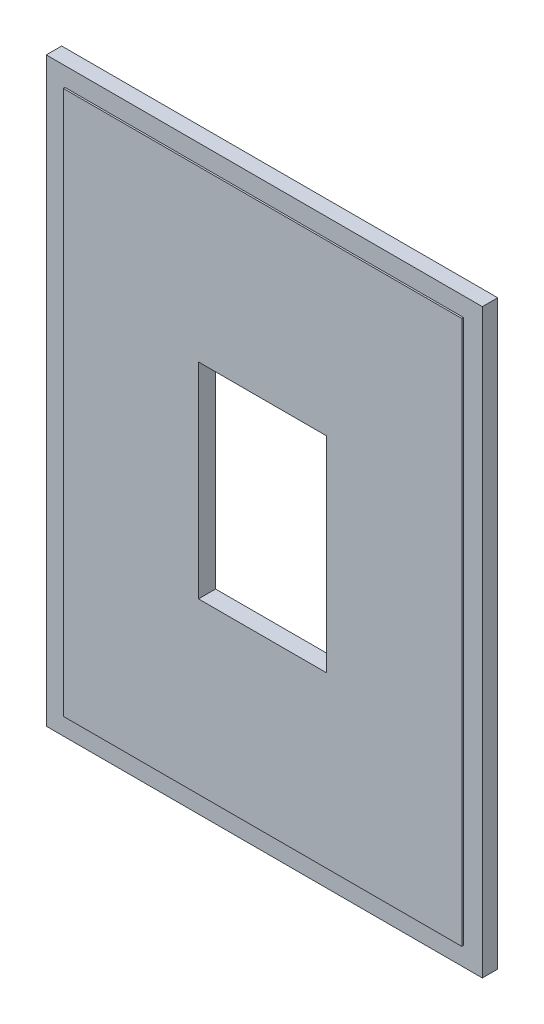
SolidWorks part; units mm, degrees
ref_plane "Plan de face" through (0, 0, 0) normal (0, 0, 1) x (1, 0, 0)
ref_plane "Plan de dessus" through (0, 0, 0) normal (0, 1, 0) x (1, 0, 0)
ref_plane "Plan de droite" through (0, 0, 0) normal (1, 0, 0) x (0, 0, -1)
sketch "Esquisse1" plane through (0, 0, 0) normal (0, 0, 1) x (1, 0, 0)
  line L1 (-127.5, 170) -> (127.5, 170)
  line L2 (-127.5, 170) -> (-127.5, -170)
  line L3 (-127.5, -170) -> (127.5, -170)
  line L4 (127.5, 170) -> (127.5, -170)
  line L5 (-127.5, 170) -> (127.5, -170) construction
  line L6 (-127.5, -170) -> (127.5, 170) construction
  point P0 (0, 0)
  dimension "D1" = 340
  dimension "D2" = 255
extrude "Boss.-Extru.1" add sketch "Esquisse1" along normal blind 10
sketch "Esquisse2" plane through (0, 0, 10) normal (0, 0, 1) x (1, 0, 0)
  line L1 (-116.5, 159) -> (116.5, 159)
  line L2 (-116.5, 159) -> (-116.5, -159)
  line L3 (-116.5, -159) -> (116.5, -159)
  line L4 (116.5, 159) -> (116.5, -159)
  line L5 (-116.5, 159) -> (116.5, -159) construction
  line L6 (-116.5, -159) -> (116.5, 159) construction
  line L7 (-127.5, 170) -> (127.5, 170)
  line L8 (-127.5, 170) -> (-127.5, -170)
  line L9 (-127.5, -170) -> (127.5, -170)
  line L10 (127.5, 170) -> (127.5, -170)
  line L11 (-127.5, 170) -> (127.5, -170) construction
  line L12 (-127.5, -170) -> (127.5, 170) construction
  point P0 (0, 0)
  point P6 (0, 0)
  dimension "D1" = 11
  dimension "D2" = 11
extrude "Enlèv. mat.-Extru.1" cut sketch "Esquisse2" against normal blind 1
sketch "Sketch1" plane through (0, 0, 10) normal (0, 0, 1) x (1, 0, 0)
  line L1 (-37.5, 60) -> (37.5, 60)
  line L2 (-37.5, 60) -> (-37.5, -60)
  line L3 (-37.5, -60) -> (37.5, -60)
  line L4 (37.5, 60) -> (37.5, -60)
  line L5 (-37.5, 60) -> (37.5, -60) construction
  line L6 (-37.5, -60) -> (37.5, 60) construction
  point P0 (0, 0)
  dimension "D1" = 120
  dimension "D2" = 75
extrude "Cut-Extrude1" cut sketch "Sketch1" against normal blind 20
